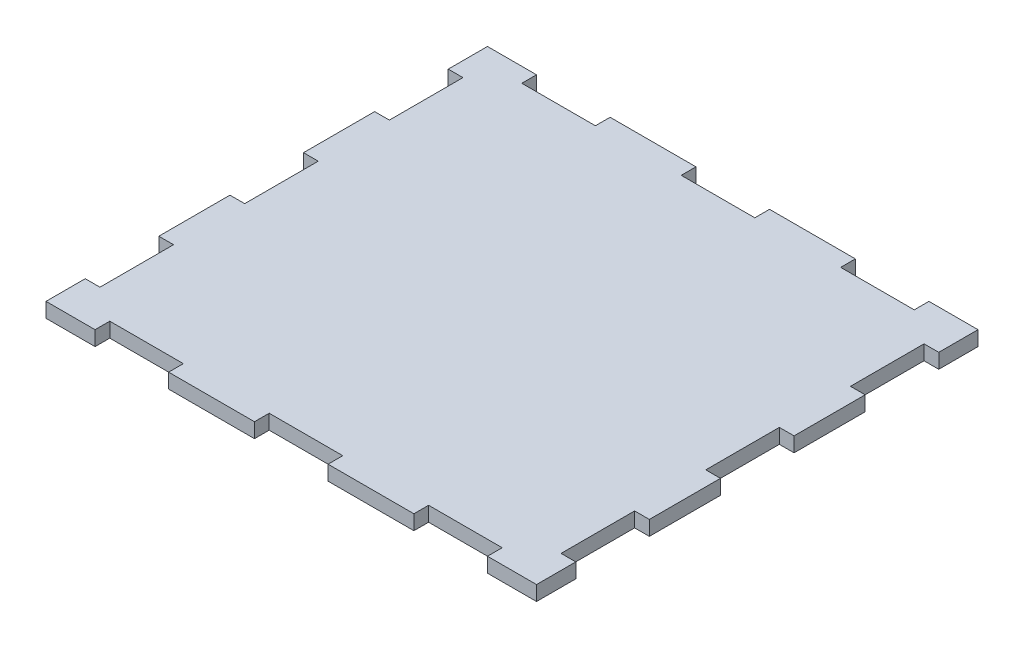
SolidWorks part; units mm, degrees
ref_plane "前视基准面" through (0, 0, 0) normal (0, 0, 1) x (1, 0, 0)
ref_plane "上视基准面" through (0, 0, 0) normal (0, 1, 0) x (1, 0, 0)
ref_plane "右视基准面" through (0, 0, 0) normal (1, 0, 0) x (0, 0, -1)
sketch "草图1" plane through (0, 0, 0) normal (0, 1, 0) x (1, 0, 0)
  line L0 (-50, 0) -> (50, 0) construction
  line L1 (-50, -45) -> (-40, -45)
  line L2 (-50, -45) -> (-50, -37)
  line L3 (-50, 45) -> (-40, 45)
  line L4 (50, -45) -> (50, -37)
  line L5 (-50, -45) -> (50, 45) construction
  line L6 (-50, 45) -> (50, -45) construction
  line L7 (25, -45) -> (25, -42)
  line L8 (-40, -45) -> (-40, -42)
  line L9 (-40, -42) -> (-25, -42)
  line L10 (-25, -45) -> (-25, -42)
  line L11 (7.5, -45) -> (25, -45)
  line L12 (-7.5, -45) -> (-7.5, -42)
  line L13 (-7.5, -42) -> (7.5, -42)
  line L14 (7.5, -45) -> (7.5, -42)
  line L15 (0, -45) -> (0, 45) construction
  line L16 (-25, -45) -> (-7.5, -45)
  line L17 (40, -45) -> (40, -42)
  line L18 (40, -42) -> (25, -42)
  line L19 (40, -45) -> (50, -45)
  line L20 (25, 45) -> (25, 42)
  line L21 (40, 45) -> (40, 42)
  line L22 (40, 42) -> (25, 42)
  line L23 (7.5, 45) -> (7.5, 42)
  line L24 (-7.5, 42) -> (7.5, 42)
  line L25 (-7.5, 45) -> (-7.5, 42)
  line L26 (-25, 45) -> (-25, 42)
  line L27 (-40, 42) -> (-25, 42)
  line L28 (-40, 45) -> (-40, 42)
  line L29 (-25, 45) -> (-7.5, 45)
  line L30 (7.5, 45) -> (25, 45)
  line L31 (40, 45) -> (50, 45)
  line L32 (-50, 7.5) -> (-50, 22)
  line L33 (-50, -37) -> (-47, -37)
  line L34 (-50, 37) -> (-47, 37)
  line L35 (-50, -22) -> (-47, -22)
  line L36 (-47, -37) -> (-47, -22)
  line L37 (-50, 7.5) -> (-47, 7.5)
  line L38 (-50, -22) -> (-50, -7.5)
  line L39 (-50, -7.5) -> (-47, -7.5)
  line L40 (-47, 7.5) -> (-47, -7.5)
  line L41 (-50, 22) -> (-47, 22)
  line L42 (-47, 37) -> (-47, 22)
  line L43 (-50, 37) -> (-50, 45)
  line L44 (50, -37) -> (47, -37)
  line L45 (47, -37) -> (47, -22)
  line L46 (50, -22) -> (47, -22)
  line L47 (50, -7.5) -> (47, -7.5)
  line L48 (47, 7.5) -> (47, -7.5)
  line L49 (50, 7.5) -> (47, 7.5)
  line L50 (50, 22) -> (47, 22)
  line L51 (47, 37) -> (47, 22)
  line L52 (50, 37) -> (47, 37)
  line L53 (50, 37) -> (50, 45)
  line L54 (50, 7.5) -> (50, 22)
  line L55 (50, -22) -> (50, -7.5)
  line L57 (-41.5, -36.5) -> (41.5, -36.5) construction
  line L58 (-41.5, -36.5) -> (-41.5, 36.5) construction
  line L59 (-41.5, 36.5) -> (41.5, 36.5) construction
  line L60 (41.5, -36.5) -> (41.5, 36.5) construction
  line L61 (-41.5, -36.5) -> (41.5, 36.5) construction
  line L62 (-41.5, 36.5) -> (41.5, -36.5) construction
  point P0 (0, 0)
  point P14 (0, -42)
  point P17 (0, 0)
  point P20 (0, 0)
  point P45 (-47, 0)
  point P62 (0, 0)
  dimension "D1" = 90
  dimension "D2" = 100
  dimension "D3" = 3
  dimension "D4" = 3
  dimension "D5" = 10
  dimension "D6" = 15
  dimension "D7" = 15
  dimension "D8" = 8
  dimension "D9" = 3
  dimension "D10" = 15
  dimension "D11" = 3
  dimension "D12" = 15
  dimension "D13" = 83
  dimension "D14" = 73
extrude "凸台-拉伸1" add sketch "草图1" along normal blind 3
